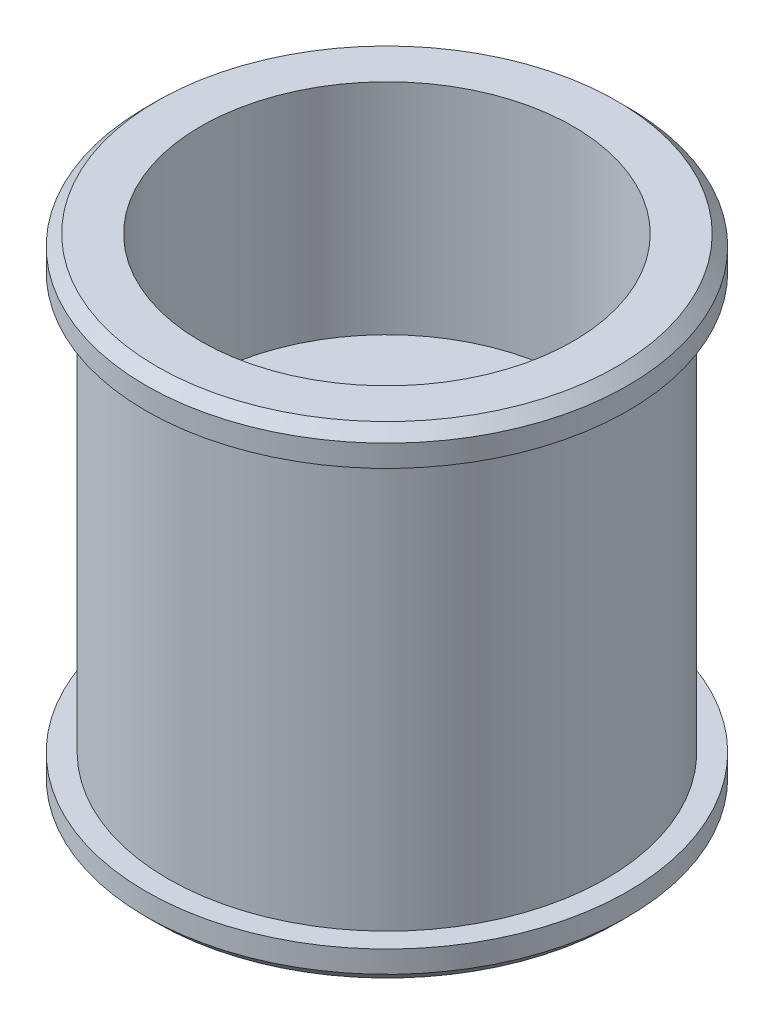
SolidWorks part; units mm, degrees
ref_plane "Спереди" through (0, 0, 0) normal (0, 0, 1) x (1, 0, 0)
ref_plane "Сверху" through (0, 0, 0) normal (0, 1, 0) x (1, 0, 0)
ref_plane "Справа" through (0, 0, 0) normal (1, 0, 0) x (0, 0, -1)
sketch "Эскиз1" plane through (0, 0, 0) normal (0, 1, 0) x (1, 0, 0)
  circle A0 centre (0, 0) radius 11
  circle A1 centre (0, 0) radius 1.5
  dimension "D1" = 22
extrude "Бобышка-Вытянуть1" add sketch "Эскиз1" along normal blind 22
sketch "Эскиз2" plane through (0, 22, 0) normal (0, 1, 0) x (1, 0, 0)
  circle A0 centre (0, 0) radius 12.5
  circle A2 centre (0, 0) radius 10
  dimension "D1" = 20
extrude "Вырез-Вытянуть1" cut sketch "Эскиз2" against normal blind 19 from offset 1.5 offset against normal yes
sketch "Эскиз3" plane through (0, 0, 0) normal (1, 0, 0) x (0, 0, -1)
  line L0 (0, 20.5) -> (0, 1.5) construction
  line L1 (-10, 20.5) -> (10, 20.5) construction
  line L2 (11, 1.5) -> (-11, 1.5) construction
  circle A0 centre (0, 4.5299) radius 1
extrude "Вырез-Вытянуть2" cut sketch "Эскиз3" against normal blind 18
chamfer "Фаска1" distance 0.5 angle 45 1 edges at (0, 0, 11)
chamfer "Фаска2" distance 0.5 angle 45 1 edges at (0, 22, 11)
sketch "Эскиз4" plane through (0, 22, 0) normal (0, 1, 0) x (1, 0, 0)
  circle A0 centre (0, 0) radius 8.5
  dimension "D1" = 17
extrude "Вырез-Вытянуть3" cut sketch "Эскиз4" against normal blind 10
